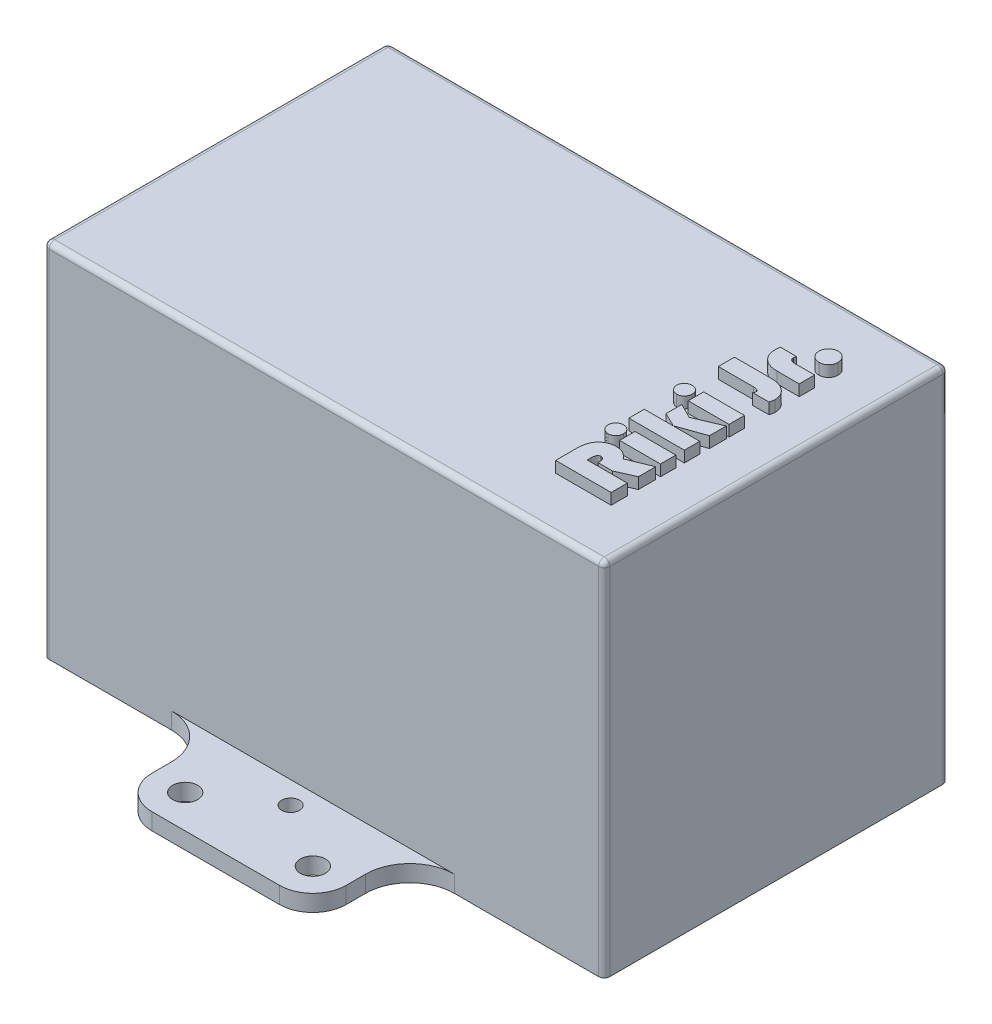
SolidWorks part; units mm, degrees
ref_plane "Front Plane" through (0, 0, 0) normal (0, 0, 1) x (1, 0, 0)
ref_plane "Top Plane" through (0, 0, 0) normal (0, 1, 0) x (1, 0, 0)
ref_plane "Right Plane" through (0, 0, 0) normal (1, 0, 0) x (0, 0, -1)
sketch "Sketch1" plane through (0, 0, 0) normal (0, 1, 0) x (1, 0, 0)
  line L0 (-50.5, -31) -> (-50.5, -7.5)
  line L1 (-48.5, -29) -> (48.5, -29)
  line L2 (-48.5, -29) -> (-48.5, -7.5)
  line L3 (-48.5, 29) -> (48.5, 29)
  line L4 (48.5, -29) -> (48.5, 29)
  line L5 (-48.5, -29) -> (48.5, 29) construction
  line L6 (-48.5, 29) -> (48.5, -29) construction
  line L7 (-50.5, 31) -> (-27.5, 31)
  line L8 (50.5, -31) -> (50.5, 31)
  line L9 (-50.5, -31) -> (-27.5, -31)
  line L10 (0, 31) -> (0, -31) construction
  line L11 (-61.8194, 0) -> (71.7366, 0) construction
  line L12 (0, 54.2187) -> (0, -48.0657) construction
  line L13 (-17.6261, -42.5) -> (34.7828, -42.5) construction
  line L14 (-17.6261, 42.5) -> (34.7828, 42.5) construction
  line L15 (23.5, -31) -> (50.5, -31)
  line L17 (-19.5, -39) -> (-19.5, -42.5)
  line L18 (-13.5, -48.5) -> (9.5, -48.5)
  line L19 (15.5, -39) -> (15.5, -42.5)
  line L20 (-50.5, -31) -> (50.5, -31) construction
  line L21 (15.5, 39) -> (15.5, 42.5)
  line L22 (-13.5, 48.5) -> (9.5, 48.5)
  line L23 (-19.5, 39) -> (-19.5, 42.5)
  line L24 (23.5, 31) -> (50.5, 31)
  line L25 (-50.5, 31) -> (50.5, 31) construction
  line L26 (-50.5, 7.5) -> (-48.5, 7.5)
  line L27 (-50.5, -7.5) -> (-48.5, -7.5)
  line L28 (-50.5, 7.5) -> (-50.5, 31)
  line L29 (-50.5, -31) -> (-50.5, 31) construction
  line L30 (-48.5, 7.5) -> (-48.5, 29)
  line L31 (-48.5, -29) -> (-48.5, 29) construction
  line L32 (-2, 59.2165) -> (-2, -52.9968) construction
  circle A0 centre (-13.5, -42.5) radius 2.25
  circle A1 centre (9.5, -42.5) radius 2.25
  circle A2 centre (9.5, 42.5) radius 2.25
  circle A3 centre (-13.5, 42.5) radius 2.25
  arc A4 (9.5, -48.5) -> (15.5, -42.5) centre (9.5, -42.5) ccw
  arc A5 (-19.5, -42.5) -> (-13.5, -48.5) centre (-13.5, -42.5) ccw
  arc A6 (23.5, -31) -> (15.5, -39) centre (23.5, -39) ccw
  arc A7 (-27.5, -31) -> (-19.5, -39) centre (-27.5, -39) cw
  arc A8 (23.5, 31) -> (15.5, 39) centre (23.5, 39) cw
  arc A9 (9.5, 48.5) -> (15.5, 42.5) centre (9.5, 42.5) cw
  arc A10 (-19.5, 42.5) -> (-13.5, 48.5) centre (-13.5, 42.5) cw
  arc A11 (-27.5, 31) -> (-19.5, 39) centre (-27.5, 39) ccw
  circle A12 centre (-2, -35) radius 1.6
  circle A13 centre (-2, 35) radius 1.6
  point P0 (0, 0)
  dimension "D4" = 4.5
  dimension "D5" = 4.5
  dimension "D12" = 6
  dimension "D13" = 8
  dimension "D9" = 11.5
  dimension "D10" = 3.2
  dimension "D1" = 97
  dimension "D2" = 58
  dimension "D6" = 35
  dimension "D7" = 39
  dimension "D8" = 85
  dimension "D11" = 6
  dimension "D14" = 15
  dimension "D3" = 2
extrude "Boss-Extrude1" add sketch "Sketch1" along normal blind 3
sketch "Sketch2" plane through (0, 3, 0) normal (0, 1, 0) x (1, 0, 0)
  line L0 (-50.5, 31) -> (-50.5, 7.5) construction
  line L1 (-48.5, -7.5) -> (-50.5, -7.5) construction
  line L2 (-50.5, -7.5) -> (-50.5, -31) construction
  line L3 (-50.5, 7.5) -> (-48.5, 7.5) construction
  line L4 (48.5, 29) -> (48.5, -29) construction
  line L5 (48.5, -29) -> (-48.5, -29) construction
  line L6 (-48.5, -29) -> (-48.5, -7.5) construction
  line L7 (-48.5, 7.5) -> (-48.5, 29) construction
  line L8 (-48.5, 29) -> (48.5, 29) construction
  line L9 (-50.5, 31) -> (-50.5, 7.5)
  line L10 (-48.5, -7.5) -> (-50.5, -7.5)
  line L11 (-50.5, -7.5) -> (-50.5, -31)
  line L12 (-50.5, 7.5) -> (-48.5, 7.5)
  line L13 (48.5, 29) -> (48.5, -29)
  line L14 (48.5, -29) -> (-48.5, -29)
  line L15 (-48.5, -29) -> (-48.5, -7.5)
  line L16 (-48.5, 7.5) -> (-48.5, 29)
  line L17 (-48.5, 29) -> (48.5, 29)
  line L18 (-50.5, 31) -> (50.5, 31)
  line L19 (50.5, 31) -> (50.5, -31)
  line L20 (50.5, -31) -> (-50.5, -31)
extrude "Boss-Extrude2" add sketch "Sketch2" along normal blind 55
sketch "Sketch3" plane through (0, 58, 0) normal (0, 1, 0) x (1, 0, 0)
  line L1 (-50.5, 31) -> (50.5, 31)
  line L2 (-50.5, 31) -> (-50.5, -31)
  line L3 (-50.5, -31) -> (50.5, -31)
  line L4 (50.5, 31) -> (50.5, -31)
  line L5 (-48.5, 29) -> (48.5, 29)
  line L6 (-48.5, 29) -> (-48.5, -29)
  line L7 (-48.5, -29) -> (48.5, -29)
  line L8 (48.5, 29) -> (48.5, -29)
extrude "Boss-Extrude3" add sketch "Sketch3" along normal blind 5
sketch "Sketch4" plane through (0, 63, 0) normal (0, 1, 0) x (1, 0, 0)
  line L1 (-50.5, 31) -> (50.5, 31)
  line L2 (-50.5, 31) -> (-50.5, -31)
  line L3 (-50.5, -31) -> (50.5, -31)
  line L4 (50.5, 31) -> (50.5, -31)
extrude "Boss-Extrude4" add sketch "Sketch4" along normal blind 2
fillet "Fillet1" radius 1 8 edges at (-50.5, 32.5, -31) (0, 65, -31) (50.5, 32.5, -31) (50.5, 65, 0) (50.5, 32.5, 31) (-50.5, 65, 0) (0, 65, 31) (-50.5, 32.5, 31)
sketch "Sketch5" plane through (0, 65, 0) normal (0, 1, 0) x (1, 0, 0)
  line L0 (42.0649, -30) -> (42.0649, 30) construction
  line L1 (-49.5, -30) -> (49.5, -30) construction
  line L2 (49.5, 30) -> (-49.5, 30) construction
  text T0 "Riki Jr." font "Bauhaus 93" height 10
extrude "Boss-Extrude5" add sketch "Sketch5" along normal blind 2
